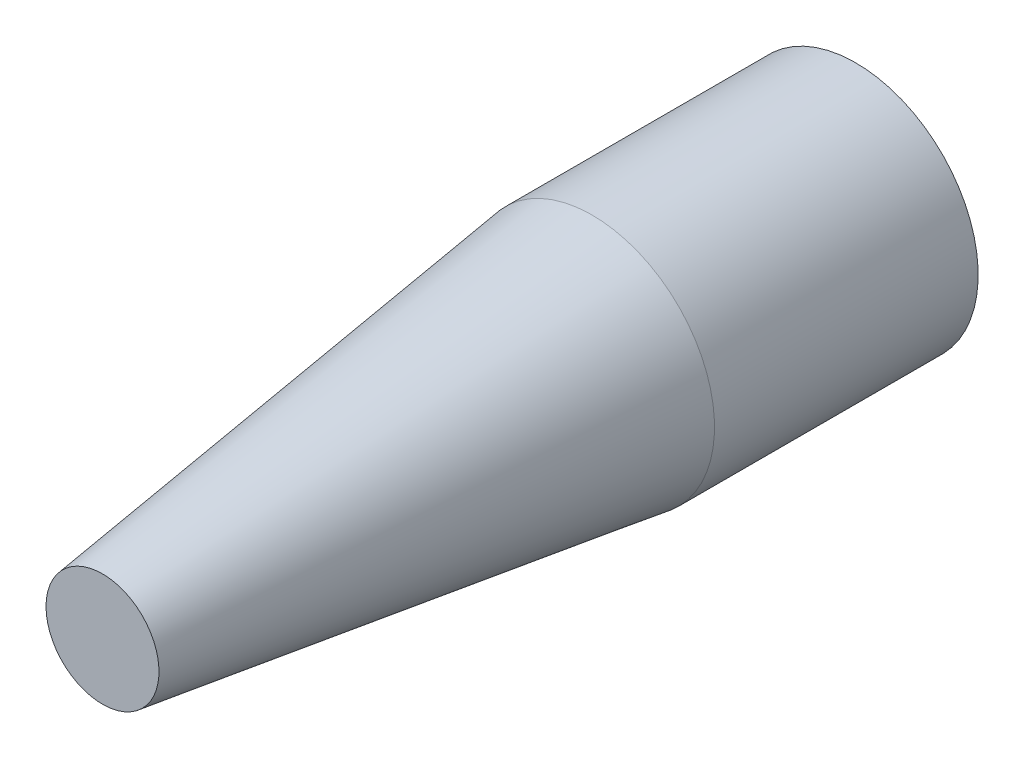
SolidWorks part; units mm, degrees
material "ABS"
ref_plane "Front" through (0, 0, 0) normal (0, 0, 1) x (1, 0, 0)
ref_plane "Top" through (0, 0, 0) normal (0, 1, 0) x (1, 0, 0)
ref_plane "Right" through (0, 0, 0) normal (1, 0, 0) x (0, 0, -1)
sketch "Эскиз1" plane through (0, 0, 0) normal (0, 1, 0) x (1, 0, 0)
  line L0 (0, 0) -> (0, -32.9133) construction
  line L1 (0, 0) -> (0, -11.2168) construction
  line L2 (0, -11.2168) -> (-1.5, -8)
  line L3 (-1.5, -8) -> (-1.5, 0)
  line L4 (-1.5, 0) -> (-3.25, 0)
  line L5 (-3.25, 0) -> (-3.25, -7)
  line L6 (-3.25, -7) -> (-1.5, -20)
  line L7 (-1.5, -20) -> (0, -20)
  line L8 (0, -20) -> (0, -11.2168)
  point P8 (0, -10.7778)
  dimension "D1" = 3
  dimension "D2" = 3
  dimension "D3" = 6.5
  dimension "D4" = 20
  dimension "D5" = 8
  dimension "D6" = 25
  dimension "D7" = 7
revolve "Повернуть2" add sketch "Эскиз1" angle 360 about L0
